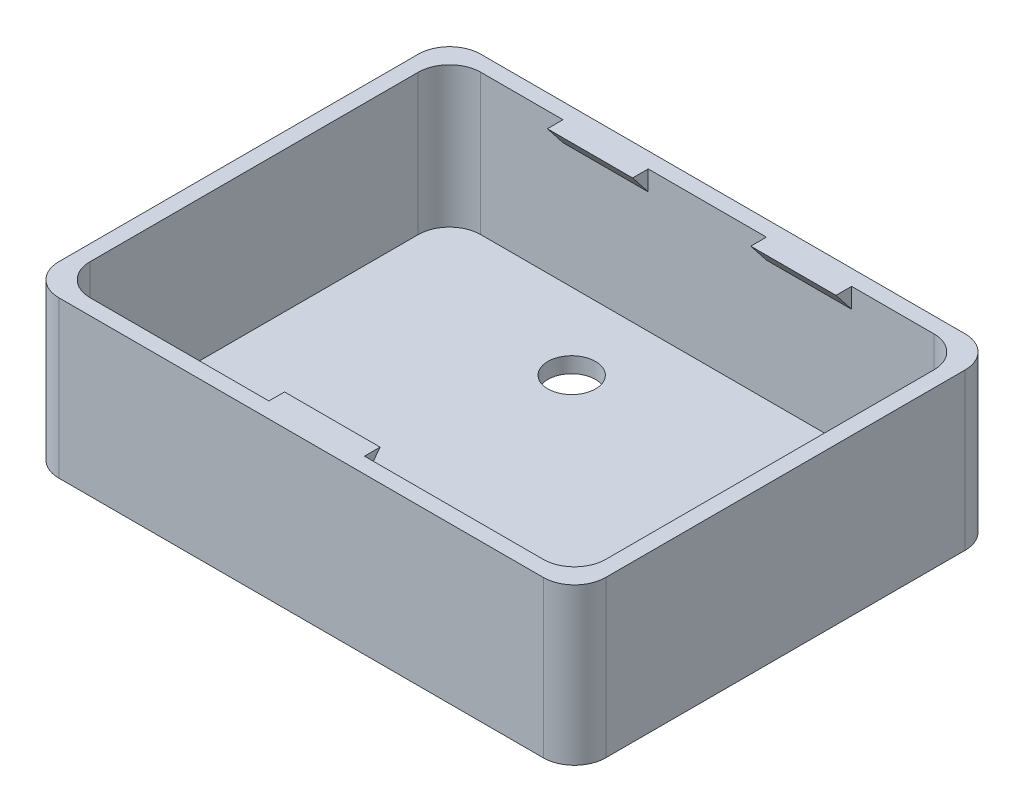
SolidWorks part; units mm, degrees
ref_plane "Front Plane" through (0, 0, 0) normal (0, 0, 1) x (1, 0, 0)
ref_plane "Top Plane" through (0, 0, 0) normal (0, 1, 0) x (1, 0, 0)
ref_plane "Right Plane" through (0, 0, 0) normal (1, 0, 0) x (0, 0, -1)
sketch "Sketch1" plane through (0, 0, 0) normal (0, 1, 0) x (1, 0, 0)
  line L1 (17.5, -13.5) -> (-17.5, -13.5)
  line L2 (17.5, -13.5) -> (17.5, 13.5)
  line L3 (17.5, 13.5) -> (-17.5, 13.5)
  line L4 (-17.5, -13.5) -> (-17.5, 13.5)
  point P0 (0, 0)
  dimension "D1" = 35
  dimension "D2" = 27
extrude "Boss-Extrude1" add sketch "Sketch1" along normal blind 10
sketch "Sketch2" plane through (0, 10, 0) normal (0, 1, 0) x (1, 0, 0)
  line L1 (16.5, -12.5) -> (-16.5, -12.5)
  line L2 (16.5, -12.5) -> (16.5, 12.5)
  line L3 (16.5, 12.5) -> (-16.5, 12.5)
  line L4 (-16.5, -12.5) -> (-16.5, 12.5)
  point P0 (0, 0)
  dimension "D1" = 25
  dimension "D2" = 33
extrude "Cut-Extrude1" cut sketch "Sketch2" against normal blind 9
sketch "Sketch3" plane through (0, 0, -12.5) normal (0, 0, 1) x (1, 0, 0)
  line L1 (16.5, 10) -> (-16.5, 10) construction
  line L2 (9.2352, 8.7268) -> (3.7813, 8.7268)
  line L3 (-9.2352, 10) -> (-3.7813, 10)
  line L4 (-9.2352, 10) -> (-9.2352, 8.7268)
  line L5 (-9.2352, 8.7268) -> (-3.7813, 8.7268)
  line L6 (-3.7813, 10) -> (-3.7813, 8.7268)
  line L7 (3.7813, 10) -> (3.7813, 8.7268)
  line L8 (9.2352, 10) -> (3.7813, 10)
  line L9 (9.2352, 10) -> (9.2352, 8.7268)
extrude "Boss-Extrude2" add sketch "Sketch3" along normal blind 1
sketch "Sketch4" plane through (0, 0, 12.5) normal (0, 0, -1) x (-1, 0, 0)
  line L1 (16.5, 10) -> (-16.5, 10) construction
  line L12 (3.0585, 8.6734) -> (-3.0585, 8.6734)
  line L13 (3.0585, 8.6734) -> (3.0585, 10)
  line L14 (3.0585, 10) -> (-3.0585, 10)
  line L15 (-3.0585, 8.6734) -> (-3.0585, 10)
  line L16 (3.0585, 8.6734) -> (-3.0585, 10) construction
  line L17 (3.0585, 10) -> (-3.0585, 8.6734) construction
extrude "Boss-Extrude5" add sketch "Sketch4" along normal blind 1 contours L13 L12 L15 L14
sketch "Sketch5" plane through (3.0585, 0, 0) normal (1, 0, 0) x (0, 0, -1)
  line L0 (-12.5, 8.6734) -> (-11.5, 10)
  line L1 (-11.5, 10) -> (-11.5, 8.6734)
  line L2 (-11.5, 8.6734) -> (-11.5, 10) construction
  line L3 (-11.5, 8.6734) -> (-12.5, 8.6734) construction
  line L4 (-11.5, 8.6734) -> (-12.5, 8.6734)
extrude "Cut-Extrude2" cut sketch "Sketch5" against normal blind 8
sketch "Sketch6" plane through (9.2352, 0, 0) normal (1, 0, 0) x (0, 0, -1)
  line L3 (11.5, 10) -> (12.5, 8.7268)
  line L4 (12.5, 8.7268) -> (11.5, 8.7268)
  line L5 (11.5, 8.7268) -> (11.5, 10)
extrude "Cut-Extrude5" cut sketch "Sketch6" against normal blind 8
sketch "Sketch7" plane through (-3.7813, 0, 0) normal (1, 0, 0) x (0, 0, -1)
  line L0 (11.5, 10) -> (12.5, 8.7268)
  line L1 (12.5, 8.7268) -> (12.5, 10) construction
  line L2 (12.5, 8.7268) -> (11.5, 8.7268)
  line L3 (11.5, 8.7268) -> (11.5, 10) construction
  line L4 (11.5, 8.7268) -> (11.5, 10)
extrude "Cut-Extrude6" cut sketch "Sketch7" against normal blind 8
fillet "Fillet1" radius 2 4 edges at (17.5, 5, -13.5) (17.5, 5, 13.5) (-17.5, 5, 13.5) (-17.5, 5, -13.5)
fillet "Fillet2" radius 2 4 edges at (-16.5, 5.5, -12.5) (16.5, 5.5, -12.5) (16.5, 5.5, 12.5) (-16.5, 5.5, 12.5)
sketch "Sketch8" plane through (0, 1, 0) normal (0, 1, 0) x (1, 0, 0)
  line L0 (-16.5, 0) -> (-3.8, 0) construction
  line L1 (-16.5, 10.5) -> (-16.5, -10.5) construction
  circle A0 centre (-3.8, -7.62) radius 1.524
  circle A1 centre (-3.8, 7.62) radius 1.524
  dimension "D3" = 3.048
  dimension "D1" = 12.7
  dimension "D2" = 7.62
extrude "Cut-Extrude7" cut sketch "Sketch8" against normal blind 8
